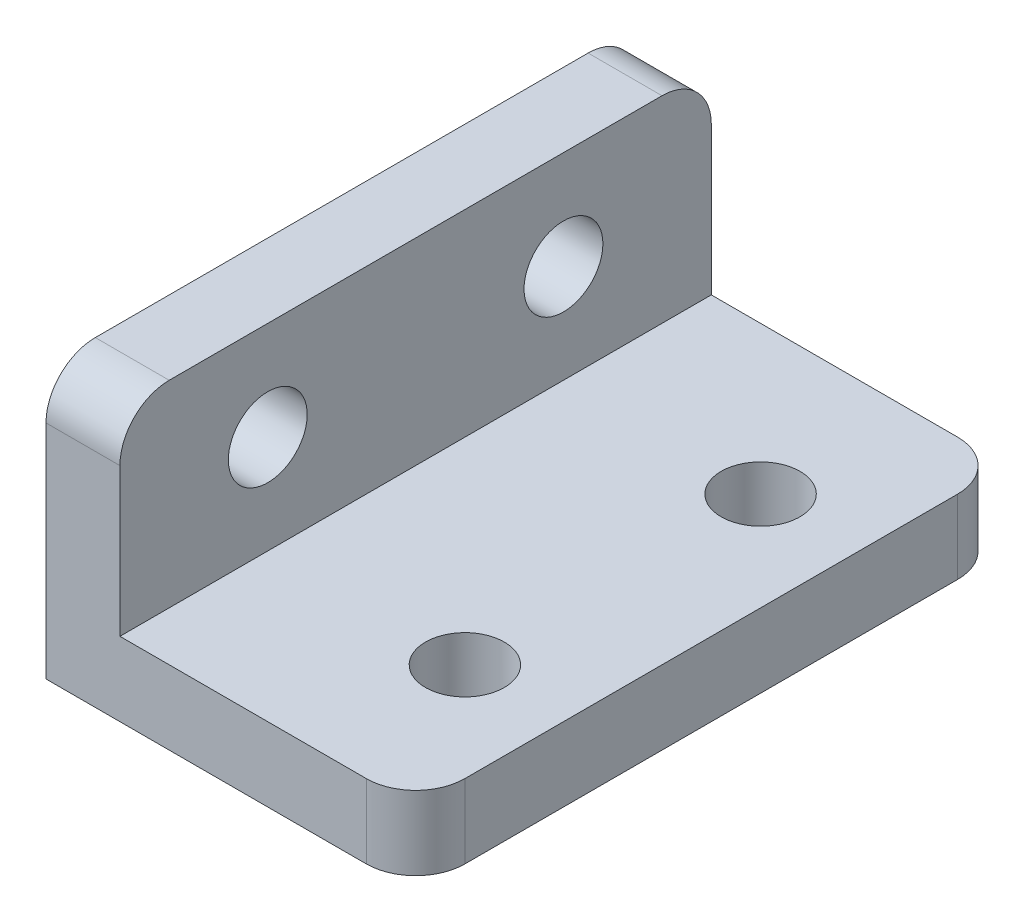
SolidWorks part; units mm, degrees
material "6061 合金"
ref_plane "前视基准面" through (0, 0, 0) normal (0, 0, 1) x (1, 0, 0)
ref_plane "上视基准面" through (0, 0, 0) normal (0, 1, 0) x (1, 0, 0)
ref_plane "右视基准面" through (0, 0, 0) normal (1, 0, 0) x (0, 0, -1)
sketch "草图1" plane through (0, 0, 0) normal (0, 0, 1) x (1, 0, 0)
  line L0 (3, 231.6916) -> (3, 101.6916) construction
  line L1 (3, 112.6916) -> (6, 112.6916)
  line L2 (3, 112.6916) -> (3, -64.3846)
  line L4 (6, 112.6916) -> (6, 104.6916)
  line L6 (3, 101.6916) -> (18, 101.6916)
  line L7 (3, 101.6916) -> (3, -61.5122)
  line L8 (6, 104.6916) -> (18, 104.6916)
  line L9 (18, 101.6916) -> (18, 104.6916)
  dimension "D1" = 3
  dimension "D2" = 3
  dimension "D3" = 8
  dimension "D4" = 12
extrude "凸台-拉伸1" add sketch "草图1" against normal blind 24 contours L6 L9 L8 L4 L1 L2 L7
sketch "草图2" plane through (6, 0, 0) normal (1, 0, 0) x (0, 0, -1)
  line L0 (24, 112.6916) -> (0, 112.6916) construction
  line L1 (0, 112.6916) -> (0, 104.6916) construction
  line L2 (24, 112.6916) -> (24, 104.6916) construction
  circle A0 centre (6, 108.6916) radius 1.6
  circle A1 centre (18, 108.6916) radius 1.6
  dimension "D1" = 3.2
  dimension "D2" = 3.2
  dimension "D3" = 4
  dimension "D4" = 6
  dimension "D5" = 6
  dimension "D6" = 4
extrude "切除-拉伸1" cut sketch "草图2" against normal blind 24
sketch "草图3" plane through (0, 104.6916, 0) normal (0, 1, 0) x (1, 0, 0)
  line L0 (18, 24) -> (18, 0) construction
  line L1 (6, 0) -> (18, 0) construction
  line L2 (6, 24) -> (18, 24) construction
  circle A0 centre (14, 6) radius 1.6
  circle A1 centre (14, 18) radius 1.6
  dimension "D1" = 3.2
  dimension "D2" = 3.2
  dimension "D3" = 4
  dimension "D4" = 4
  dimension "D5" = 6
  dimension "D6" = 6
extrude "切除-拉伸2" cut sketch "草图3" against normal blind 24
fillet "圆角1" radius 2 4 edges at (18, 103.1916, -24) (18, 103.1916, 0) (4.5, 112.6916, -24) (4.5, 112.6916, 0)
